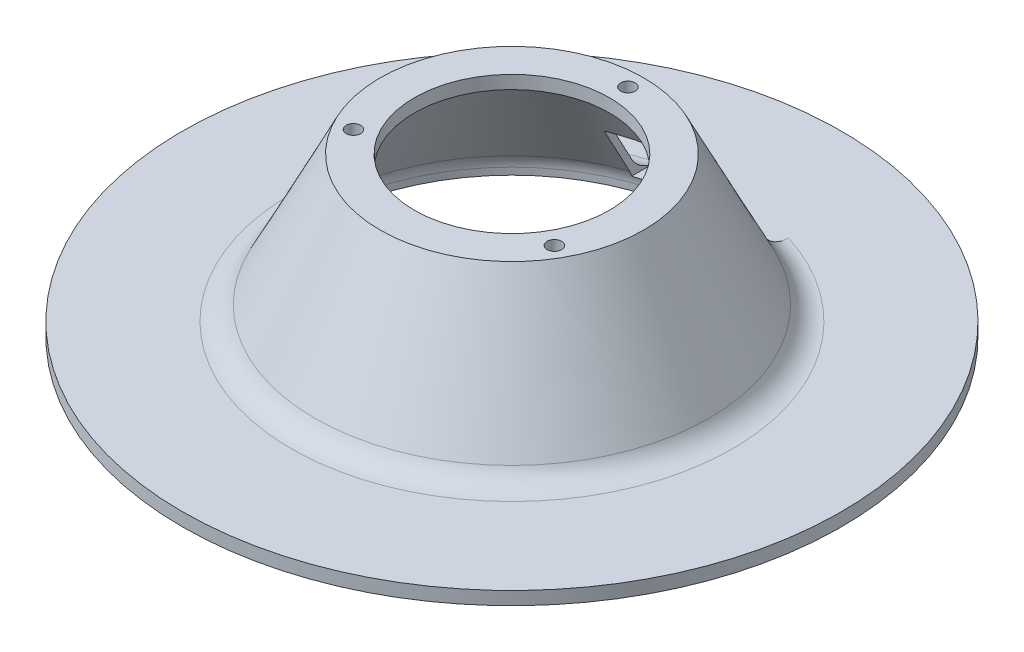
SolidWorks part; units mm, degrees
ref_plane "Front Plane" through (0, 0, 0) normal (0, 0, 1) x (1, 0, 0)
ref_plane "Top Plane" through (0, 0, 0) normal (0, 1, 0) x (1, 0, 0)
ref_plane "Right Plane" through (0, 0, 0) normal (1, 0, 0) x (0, 0, -1)
sketch "Sketch1" plane through (0, 0, 0) normal (0, 1, 0) x (1, 0, 0)
  circle A0 centre (0, 0) radius 44 construction
  circle A1 centre (0, 44) radius 2.75
  circle A2 centre (38.1051, -22) radius 2.75
  circle A3 centre (-38.1051, -22) radius 2.75
  circle A4 centre (0, 0) radius 37
  circle A5 centre (0, 0) radius 50
  point P11 (0, 0)
  dimension "D1" = 88
  dimension "D3" = 5.5
  dimension "D4" = 74
  dimension "D5" = 100
  dimension "D2" = 3
extrude "Boss-Extrude1" add sketch "Sketch1" along normal blind 5
ref_plane "Plane1" through (0, -55, 0) normal (0, 1, 0) x (1, 0, 0)
sketch "Sketch2" plane through (0, -55, 0) normal (0, 1, 0) x (1, 0, 0)
  circle A0 centre (0, 0) radius 125
  circle A1 centre (0, 0) radius 75
  dimension "D1" = 250
  dimension "D2" = 150
extrude "Boss-Extrude2" add sketch "Sketch2" along normal blind 5 separate body
sketch "Sketch3" plane through (0, 0, 0) normal (0, 0, 1) x (1, 0, 0)
  line L0 (-50, 0) -> (-75, -50)
  line L1 (-50, 5) -> (-77.5, -50)
  line L2 (-50, 5) -> (-50, 0)
  line L3 (-77.5, -50) -> (-75, -50)
  line L4 (0, 0) -> (0, -50) construction
  point P9 (0, -50)
revolve "Revolve1" add sketch "Sketch3" angle 360 about L4
fillet "Fillet1" radius 10 2 edges at (0, -50, 77.5) (0, -50, 75)
sketch "Sketch4" plane through (0, 0, 0) normal (0, 0, 1) x (1, 0, 0)
  line L1 (-25, -30) -> (25, -30)
  line L2 (-25, -30) -> (-25, -50)
  line L3 (-25, -50) -> (25, -50)
  line L4 (25, -30) -> (25, -50)
  line L5 (125, -50) -> (-125, -50) construction
  point P6 (0, -30)
  point P8 (-54.6979, -39.5388)
  dimension "D1" = 50
  dimension "D2" = 20
extrude "Cut-Extrude1" cut sketch "Sketch4" against normal through all
